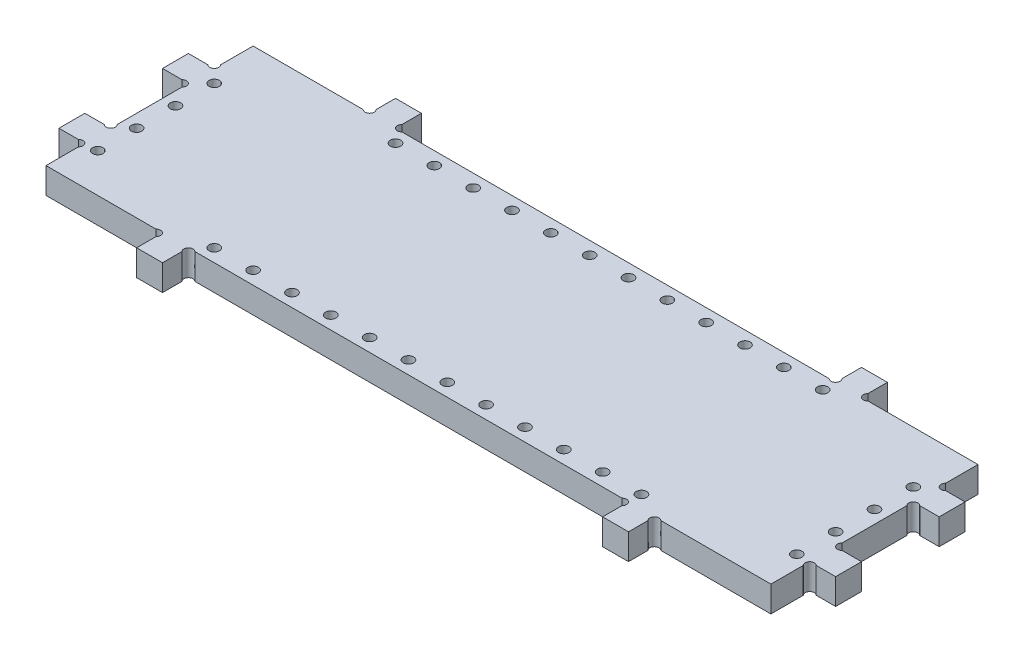
SolidWorks part; units mm, degrees
material "6061 Alloy"
ref_plane "Front" through (0, 0, 0) normal (0, 0, 1) x (1, 0, 0)
ref_plane "Top" through (0, 0, 0) normal (0, 1, 0) x (1, 0, 0)
ref_plane "Right" through (0, 0, 0) normal (1, 0, 0) x (0, 0, -1)
sketch "Sketch2" plane through (0, 0, 0) normal (0, 1, 0) x (1, 0, 0)
  line L1 (-177.8, -50.8) -> (177.8, -50.8)
  line L2 (-177.8, -50.8) -> (-177.8, 50.8)
  line L3 (-177.8, 50.8) -> (177.8, 50.8)
  line L4 (177.8, -50.8) -> (177.8, 50.8)
  line L5 (-177.8, -50.8) -> (177.8, 50.8) construction
  line L6 (-177.8, 50.8) -> (177.8, -50.8) construction
  point P0 (0, 0)
  dimension "D1" = 355.6
  dimension "D2" = 101.6
extrude "Rectangle Extrusion" add sketch "Sketch2" along normal blind 12.7
sketch "Sketch4" plane through (0, 0, 50.8) normal (0, 0, 1) x (1, 0, 0)
  line L0 (-177.8, 12.7) -> (-114.3, 12.7) construction
  line L1 (-177.8, 12.7) -> (177.8, 12.7) construction
  line L2 (-114.3, 12.7) -> (-114.3, 6.35) construction
  line L3 (-177.8, 0) -> (177.8, 0) construction
  line L4 (-107.95, 12.7) -> (-120.65, 12.7)
  line L5 (-107.95, 12.7) -> (-107.95, 0)
  line L6 (-107.95, 0) -> (-120.65, 0)
  line L7 (-120.65, 12.7) -> (-120.65, 0)
  line L8 (-107.95, 12.7) -> (-120.65, 0) construction
  line L9 (-107.95, 0) -> (-120.65, 12.7) construction
  line L10 (0, 12.7) -> (0, 0) construction
  line L11 (107.95, 0) -> (120.65, 0)
  line L12 (120.65, 12.7) -> (120.65, 0)
  line L13 (107.95, 12.7) -> (120.65, 12.7)
  line L14 (107.95, 12.7) -> (107.95, 0)
  dimension "D1" = 63.5
  dimension "D2" = 6.35
  dimension "D3" = 12.7
extrude "Front Face Tabs" add sketch "Sketch4" along normal blind 12.7
mirror "Mirror Rear Face Tabs" about plane through (0, 0, 0) normal (0, 0, 1) of "Front Face Tabs"
sketch "Sketch6" plane through (0, 12.7, 0) normal (0, 1, 0) x (1, 0, 0)
  line L0 (-120.65, 50.8) -> (-177.8, 50.8) construction
  line L1 (-120.65, 63.5) -> (-120.65, 50.8) construction
  line L2 (-114.3, 63.5) -> (-114.3, 50.1421) construction
  line L3 (-107.95, 63.5) -> (-120.65, 63.5) construction
  line L4 (0, -55) -> (0, 55) construction
  line L5 (-55, 0) -> (55, 0) construction
  circle A0 centre (-122.2375, 52.3875) radius 2.2454
  circle A1 centre (-106.3625, 52.3875) radius 2.2454
  circle A2 centre (106.3625, 52.3875) radius 2.2454
  circle A3 centre (122.2375, 52.3875) radius 2.2454
  circle A4 centre (122.2375, -52.3875) radius 2.2454
  circle A5 centre (106.3625, -52.3875) radius 2.2454
  circle A6 centre (-106.3625, -52.3875) radius 2.2454
  circle A7 centre (-122.2375, -52.3875) radius 2.2454
  dimension "D1" = 1.5875
  dimension "D3" = 4.4907
  dimension "D2" = 1.5875
extrude "Tab Curve Front Back" cut sketch "Sketch6" against normal up to surface (12.7 mm away) up to face at (0, 0, 0)
sketch "Sketch7" plane through (177.8, 0, 0) normal (1, 0, 0) x (0, 0, -1)
  line L0 (-50.8, 12.7) -> (-25.4, 12.7) construction
  line L1 (-50.8, 12.7) -> (50.8, 12.7) construction
  line L2 (-25.4, 12.7) -> (-25.4, 0) construction
  line L3 (55, 0) -> (-55, 0) construction
  line L4 (0, 55) -> (0, -55) construction
  line L5 (-31.75, 12.7) -> (-19.05, 12.7)
  line L6 (-31.75, 12.7) -> (-31.75, 0)
  line L7 (-31.75, 0) -> (-19.05, 0)
  line L8 (-19.05, 12.7) -> (-19.05, 0)
  line L9 (-31.75, 12.7) -> (-19.05, 0) construction
  line L10 (-31.75, 0) -> (-19.05, 12.7) construction
  line L11 (31.75, 0) -> (19.05, 0)
  line L12 (19.05, 12.7) -> (19.05, 0)
  line L13 (31.75, 12.7) -> (19.05, 12.7)
  line L14 (31.75, 12.7) -> (31.75, 0)
  point P5 (-25.4, 6.35)
  dimension "D1" = 25.4
  dimension "D2" = 12.7
extrude "Right Face Tabs" add sketch "Sketch7" along normal blind 12.7
mirror "Mirror Left Face Tabs" about plane through (0, 0, 0) normal (1, 0, 0) of "Right Face Tabs"
sketch "Sketch8" plane through (0, 12.7, 0) normal (0, 1, 0) x (1, 0, 0)
  line L0 (190.5, 31.75) -> (177.8, 31.75) construction
  line L1 (177.8, 31.75) -> (177.8, 50.8) construction
  line L2 (190.5, 25.4) -> (126.2032, 25.4) construction
  line L3 (190.5, 31.75) -> (190.5, 19.05) construction
  line L4 (-55, 0) -> (55, 0) construction
  line L5 (0, -55) -> (0, 55) construction
  circle A0 centre (179.3875, 33.3375) radius 2.2454
  circle A1 centre (179.3875, 17.4625) radius 2.2454
  circle A2 centre (179.3875, -17.4625) radius 2.2454
  circle A3 centre (179.3875, -33.3375) radius 2.2454
  circle A4 centre (-179.3875, -33.3375) radius 2.2454
  circle A5 centre (-179.3875, -17.4625) radius 2.2454
  circle A6 centre (-179.3875, 17.4625) radius 2.2454
  circle A7 centre (-179.3875, 33.3375) radius 2.2454
  dimension "D3" = 4.4907
  dimension "D1" = 1.5875
  dimension "D2" = 1.5875
extrude "Tab Curve Left Right" cut sketch "Sketch8" against normal up to surface (12.7 mm away) up to face at (0, 0, 0)
sketch "Sketch9" plane through (0, 0, 0) normal (0, -1, 0) x (1, 0, 0)
  line L0 (-177.8, 44.45) -> (177.8, 44.45) construction
  line L1 (-177.8, 34.9254) -> (-177.8, 50.8) construction
  line L2 (177.8, 50.8) -> (177.8, 34.9254) construction
  line L3 (-177.8, 50.8) -> (-123.8254, 50.8) construction
  line L4 (-177.8, 0) -> (177.8, 0) construction
  line L5 (-177.8, -15.8746) -> (-177.8, 15.8746) construction
  line L6 (177.8, 15.8746) -> (177.8, -15.8746) construction
  line L7 (171.45, 50.8) -> (171.45, -50.8) construction
  line L8 (123.8254, 50.8) -> (177.8, 50.8) construction
  line L9 (177.8, -50.8) -> (123.8254, -50.8) construction
  line L10 (0, 50.8) -> (0, -50.8) construction
  line L11 (-104.7746, 50.8) -> (104.7746, 50.8) construction
  line L12 (104.7746, -50.8) -> (-104.7746, -50.8) construction
  circle A0 centre (-101.6, 44.45) radius 2.5527
  circle A32 centre (-82.55, 44.45) radius 2.5527
  circle A33 centre (-63.5, 44.45) radius 2.5527
  circle A34 centre (-44.45, 44.45) radius 2.5527
  circle A35 centre (-25.4, 44.45) radius 2.5527
  circle A36 centre (-6.35, 44.45) radius 2.5527
  circle A37 centre (12.7, 44.45) radius 2.5527
  circle A38 centre (31.75, 44.45) radius 2.5527
  circle A39 centre (50.8, 44.45) radius 2.5527
  circle A40 centre (69.85, 44.45) radius 2.5527
  circle A41 centre (88.9, 44.45) radius 2.5527
  circle A42 centre (107.95, 44.45) radius 2.5527
  circle A43 centre (107.95, -44.45) radius 2.5527
  circle A44 centre (88.9, -44.45) radius 2.5527
  circle A45 centre (69.85, -44.45) radius 2.5527
  circle A46 centre (50.8, -44.45) radius 2.5527
  circle A47 centre (31.75, -44.45) radius 2.5527
  circle A48 centre (12.7, -44.45) radius 2.5527
  circle A49 centre (-6.35, -44.45) radius 2.5527
  circle A50 centre (-25.4, -44.45) radius 2.5527
  circle A51 centre (-44.45, -44.45) radius 2.5527
  circle A52 centre (-63.5, -44.45) radius 2.5527
  circle A53 centre (-82.55, -44.45) radius 2.5527
  circle A54 centre (-101.6, -44.45) radius 2.5527
  circle A55 centre (171.45, -25.4) radius 2.5527
  circle A56 centre (171.45, -6.35) radius 2.5527
  circle A57 centre (171.45, 12.7) radius 2.5527
  circle A58 centre (171.45, 31.75) radius 2.5527
  circle A59 centre (-171.45, -25.4) radius 2.5527
  circle A60 centre (-171.45, -6.35) radius 2.5527
  circle A61 centre (-171.45, 12.7) radius 2.5527
  circle A62 centre (-171.45, 31.75) radius 2.5527
  point P64 (-127, 50.8)
  dimension "D2" = 76.2
  dimension "D3" = 5.1054
  dimension "D5" = 19.05
  dimension "D7" = 25.4
  dimension "D8" = 5.1054
  dimension "D10" = 19.05
  dimension "D1" = 6.35
  dimension "D6" = 6.35
  dimension "D4" = 12
  dimension "D9" = 4
extrude "Cut-Extrude1" cut sketch "Sketch9" against normal through all
